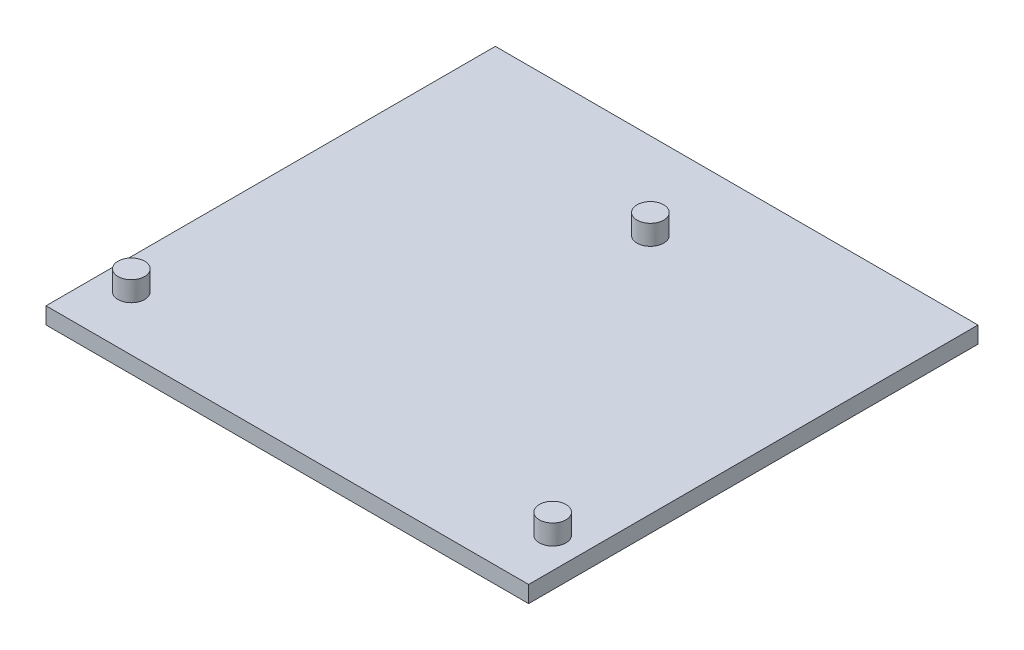
SolidWorks part; units mm, degrees
ref_plane "Front Plane" through (0, 0, 0) normal (0, 0, 1) x (1, 0, 0)
ref_plane "Top Plane" through (0, 0, 0) normal (0, 1, 0) x (1, 0, 0)
ref_plane "Right Plane" through (0, 0, 0) normal (1, 0, 0) x (0, 0, -1)
sketch "Sketch1" plane through (0, 0, 0) normal (0, 1, 0) x (1, 0, 0)
  line L1 (-14.5, -13.5) -> (14.5, -13.5)
  line L2 (-14.5, -13.5) -> (-14.5, 13.5)
  line L3 (-14.5, 13.5) -> (14.5, 13.5)
  line L4 (14.5, -13.5) -> (14.5, 13.5)
  line L5 (-14.5, -13.5) -> (14.5, 13.5) construction
  line L6 (-14.5, 13.5) -> (14.5, -13.5) construction
  point P0 (0, 0)
  dimension "D1" = 29
  dimension "D2" = 27
extrude "Boss-Extrude1" add sketch "Sketch1" along normal blind 1
sketch "Sketch2" plane through (0, 1, 0) normal (0, 1, 0) x (1, 0, 0)
  line L0 (0, -0.55) -> (0, 0.55) construction
  line L1 (-12.66, -10.2152) -> (12.66, -10.2152) construction
  circle A0 centre (0, 8.3148) radius 0.8
  circle A1 centre (-12.66, -10.2152) radius 0.8
  circle A2 centre (12.66, -10.2152) radius 0.8
  dimension "D3" = 1.6
  dimension "D4" = 1.6
  dimension "D5" = 1.6
  dimension "D1" = 25.32
  dimension "D2" = 12.66
  dimension "D6" = 18.53
  dimension "D7" = 22.4418
extrude "Boss-Extrude2" add sketch "Sketch2" along normal blind 1.2
